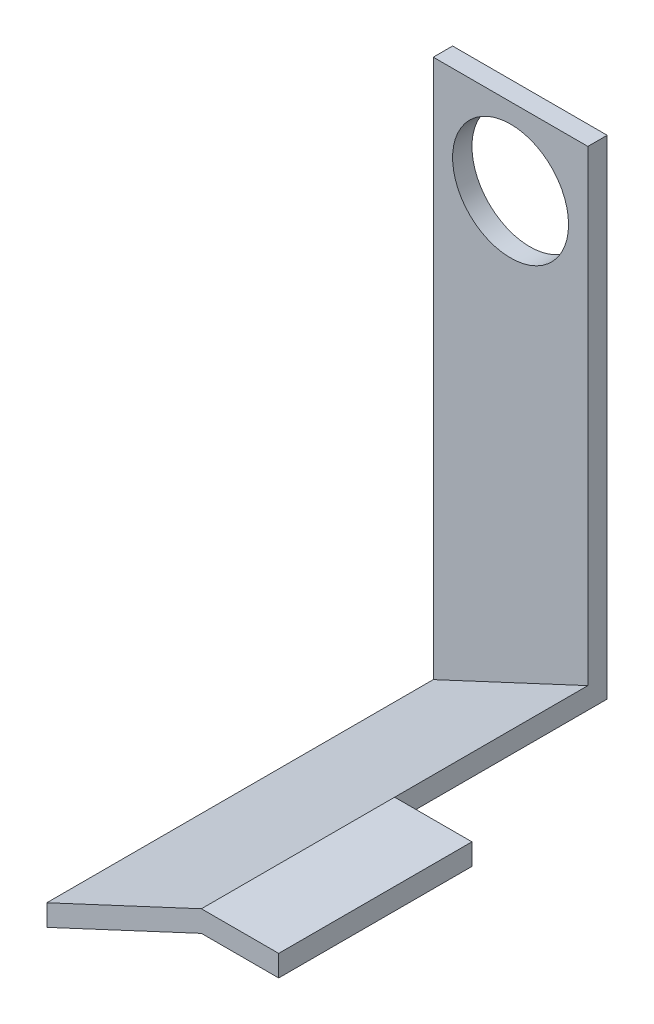
SolidWorks part; units mm, degrees
ref_plane "Front" through (0, 0, 0) normal (0, 0, 1) x (1, 0, 0)
ref_plane "Top" through (0, 0, 0) normal (0, 1, 0) x (1, 0, 0)
ref_plane "Right" through (0, 0, 0) normal (1, 0, 0) x (0, 0, -1)
sketch "Эскиз4" plane through (0, 0, 0) normal (0, 0, 1) x (1, 0, 0)
  line L0 (-2, -8.5) -> (2, -6.6348)
  line L2 (-2, -8.5) -> (-2, 6)
  line L3 (-2, 6) -> (2, 6)
  line L4 (2, -6.6348) -> (2, 6)
  circle A0 centre (0, 4) radius 1.5
  point P0 (0, 0)
  dimension "D1" = 4
  dimension "D2" = 2
  dimension "D4" = 14.5
  dimension "D5" = 65
extrude "Бобышка-Вытянуть3" add sketch "Эскиз4" along normal blind 0.5
sketch "Эскиз5" plane through (0, 0, 0.5) normal (0, 0, 1) x (1, 0, 0)
  line L0 (-2, -8.5) -> (2, -6.6348)
  line L1 (2, -6.6348) -> (2, -6.0831)
  line L3 (2, -6.0831) -> (-2, -7.9483)
  line L4 (-2, 6) -> (-2, -8.5) construction
  line L5 (-2, -7.9483) -> (-2, -8.5)
  line L6 (2, -6.6348) -> (2, 6) construction
  dimension "D1" = 0.5
extrude "Бобышка-Вытянуть4" add sketch "Эскиз5" along normal blind 10
sketch "Эскиз6" plane through (2, 0, 0) normal (1, 0, 0) x (0, 0, -1)
  line L0 (-10.5, -6.6348) -> (0, -6.6348) construction
  line L1 (-10.5, -6.0831) -> (-5.5, -6.0831)
  line L2 (-10.5, -6.0831) -> (-10.5, -6.6348)
  line L3 (-10.5, -6.6348) -> (-5.5, -6.6348)
  line L4 (-5.5, -6.0831) -> (-5.5, -6.6348)
  dimension "D1" = 5
extrude "Бобышка-Вытянуть5" add sketch "Эскиз6" along normal blind 2
